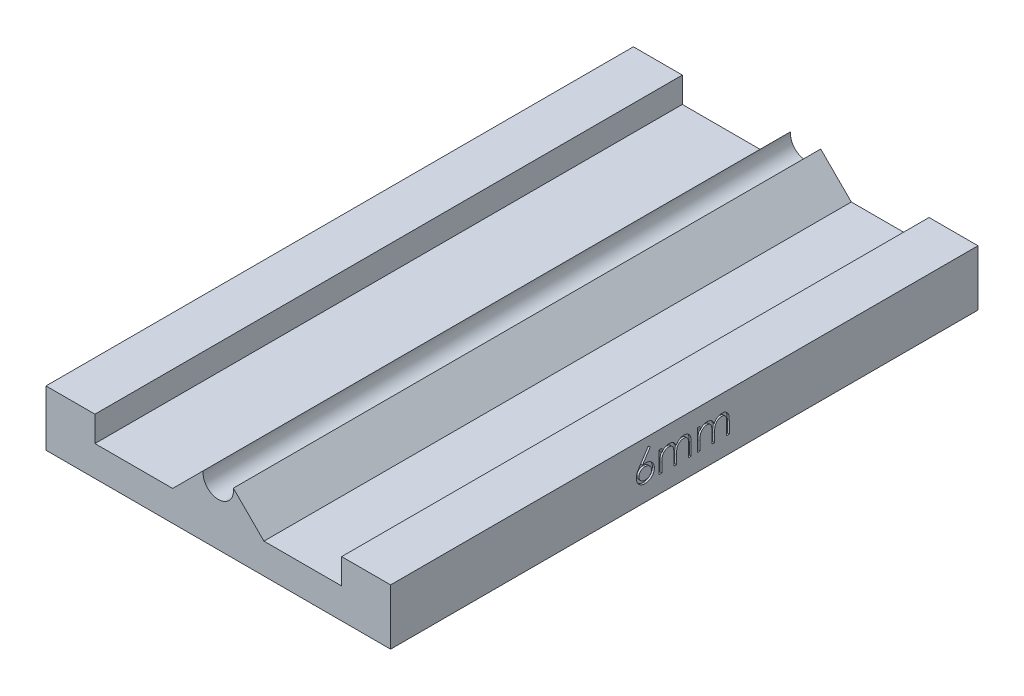
SolidWorks part; units mm, degrees
ref_plane "Front Plane" through (0, 0, 0) normal (0, 0, 1) x (1, 0, 0)
ref_plane "Top Plane" through (0, 0, 0) normal (0, 1, 0) x (1, 0, 0)
ref_plane "Right Plane" through (0, 0, 0) normal (1, 0, 0) x (0, 0, -1)
sketch "Sketch1" plane through (0, 0, 0) normal (0, 0, 1) x (1, 0, 0)
  line L0 (0, 0) -> (0, 4.3841) construction
  line L1 (0, 4.3841) -> (-10, -5.6159)
  line L2 (0, 4.3841) -> (10, -5.6159)
  line L3 (-10, -5.6159) -> (-25, -5.6159)
  line L4 (-25, -5.6159) -> (-25, 14.3841)
  line L5 (-25, 14.3841) -> (25, 14.3841)
  line L6 (25, 14.3841) -> (25, -5.6159)
  line L7 (25, -5.6159) -> (10, -5.6159)
  line L8 (-35.2, -0.6159) -> (-35.2, -12)
  line L9 (-35.2, -12) -> (35.2, -12)
  line L10 (35.2, -12) -> (35.2, -0.6159)
  line L11 (35.2, -0.6159) -> (25.2, -0.6159)
  line L12 (25.2, -0.6159) -> (25.2, -5.8159)
  line L13 (-25.2, -5.8159) -> (-9.3204, -5.8159)
  line L14 (-35.2, -0.6159) -> (-25.2, -0.6159)
  line L15 (-25.2, -0.6159) -> (-25.2, -5.8159)
  line L16 (25.2, -5.8159) -> (9.3204, -5.8159)
  line L17 (-9.3204, -5.8159) -> (-3.0693, 0.4351)
  line L18 (9.3204, -5.8159) -> (3.0693, 0.4351)
  circle A0 centre (0, 0) radius 3.1
  dimension "D12" = 6.2
  dimension "D1" = 45
  dimension "D2" = 10
  dimension "D3" = 20
  dimension "D4" = 50
  dimension "D5" = 25
  dimension "D6" = 5
  dimension "D7" = 0.2
  dimension "D8" = 0.2
  dimension "D9" = 5
  dimension "D10" = 10
  dimension "D11" = 10
  dimension "D13" = 12
  dimension "D14" = 0.2
  dimension "D15" = 0.2
extrude "Boss-Extrude1" add sketch "Sketch1" along normal blind 120 contours A0 L17 L13 L15 L14 L8 L9 L10 L11 L12 L16 L18
sketch "Sketch2" plane through (35.2, 0, 0) normal (1, 0, 0) x (0, 0, -1)
  text T0 "6mm" font "Century Gothic" height 6
extrude "Cut-Extrude1" cut sketch "Sketch2" against normal blind 0.4
